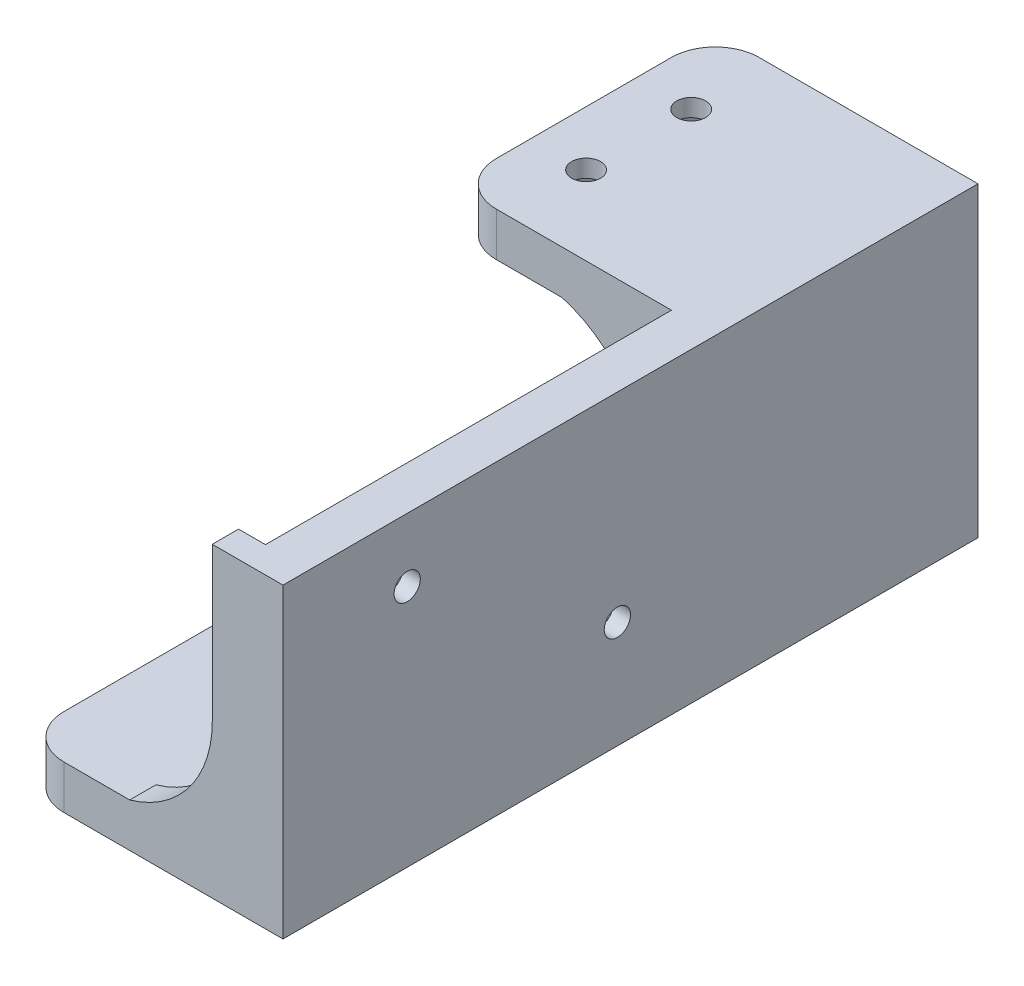
SolidWorks part; units mm, degrees
ref_plane "Спереди" through (0, 0, 0) normal (0, 0, 1) x (1, 0, 0)
ref_plane "Сверху" through (0, 0, 0) normal (0, 1, 0) x (1, 0, 0)
ref_plane "Справа" through (0, 0, 0) normal (1, 0, 0) x (0, 0, -1)
sketch "Эскиз1" plane through (0, 0, 0) normal (0, 0, 1) x (1, 0, 0)
  line L0 (0, 0) -> (30, 0)
  line L1 (30, 0) -> (30, 35)
  line L2 (30, 35) -> (0, 35)
  line L3 (0, 35) -> (0, 30)
  line L4 (0, 30) -> (25, 30)
  line L5 (25, 30) -> (25, 5)
  line L6 (25, 5) -> (0, 5)
  line L7 (0, 5) -> (0, 0)
  dimension "D1" = 35
  dimension "D2" = 5
  dimension "D3" = 5
  dimension "D4" = 5
  dimension "D5" = 30
extrude "Бобышка-Вытянуть1" add sketch "Эскиз1" along normal blind 30
sketch "Эскиз2" plane through (0, 0, 30) normal (0, 0, 1) x (1, 0, 0)
  line L0 (0, 30) -> (25, 30) construction
  line L1 (25, 5) -> (0, 5) construction
  line L2 (12.5, 30) -> (25, 30)
  line L3 (25, 30) -> (25, 5)
  line L4 (25, 5) -> (12.5, 5)
  arc A0 (12.5, 30) -> (12.5, 5) centre (8.9293, 17.5) cw
  dimension "D1" = 13
extrude "Бобышка-Вытянуть2" add sketch "Эскиз2" against normal blind 3
ref_plane "Плоскость1" through (0, 0, 15) normal (0, 0, 1) x (1, 0, 0)
mirror "Зеркальное отражение1" about plane through (0, 0, 15) normal (0, 0, 1) of "Бобышка-Вытянуть2"
sketch "Эскиз3" plane through (0, 5, 0) normal (0, 1, 0) x (1, 0, 0)
  line L0 (12.5, -3) -> (0, -3) construction
  line L1 (0, -30) -> (0, 0) construction
  line L2 (0, -3) -> (25, -27) construction
  line L3 (25, -15) -> (0, -15) construction
  line L4 (4.5179, -24) -> (2.7859, -21)
  line L5 (2.7859, -9) -> (4.5179, -12)
  line L6 (4.5179, -12) -> (7.9821, -12)
  line L7 (7.9821, -12) -> (9.7141, -9)
  line L8 (9.7141, -9) -> (7.9821, -6)
  line L9 (7.9821, -6) -> (4.5179, -6)
  line L10 (4.5179, -6) -> (2.7859, -9)
  line L17 (7.9821, -24) -> (4.5179, -24)
  line L18 (9.7141, -21) -> (7.9821, -24)
  line L19 (7.9821, -18) -> (9.7141, -21)
  line L20 (4.5179, -18) -> (7.9821, -18)
  line L21 (2.7859, -21) -> (4.5179, -18)
  circle A0 centre (6.25, -9) radius 3 construction
  point P10 (12.5, -15)
  dimension "D1" = 6
  dimension "D2" = 6
extrude "Вырез-Вытянуть1" cut sketch "Эскиз3" against normal blind 3
sketch "Эскиз4" plane through (0, 2, 0) normal (0, 1, 0) x (1, 0, 0)
  circle A0 centre (6.25, -21) radius 3.4641 construction
  circle A1 centre (6.25, -21) radius 1.65
  dimension "D1" = 3.3
extrude "Вырез-Вытянуть2" cut sketch "Эскиз4" against normal blind 17 and the other way blind 59
mirror "Зеркальное отражение2" about plane through (0, 0, 15) normal (0, 0, 1) of "Вырез-Вытянуть2"
sketch "Эскиз5" plane through (0, 30, 0) normal (0, -1, 0) x (1, 0, 0)
  line L1 (9.7141, 21) -> (7.9821, 24)
  line L2 (7.9821, 24) -> (4.5179, 24)
  line L3 (4.5179, 24) -> (2.7859, 21)
  line L4 (2.7859, 21) -> (4.5179, 18)
  line L5 (4.5179, 18) -> (7.9821, 18)
  line L6 (7.9821, 18) -> (9.7141, 21)
  circle A0 centre (6.25, 21) radius 3 construction
  dimension "D1" = 6
extrude "Вырез-Вытянуть3" cut sketch "Эскиз5" against normal blind 3
mirror "Зеркальное отражение3" about plane through (0, 0, 15) normal (0, 0, 1) of "Вырез-Вытянуть3"
fillet "Скругление1" radius 5 3 edges at (0, 32.5, 0) (0, 32.5, 30) (0, 2.5, 0)
sketch "Эскиз7" plane through (0, 0, 30) normal (0, 0, 1) x (1, 0, 0)
  line L0 (0, 0) -> (30, 0)
  line L1 (30, 0) -> (30, 35)
  line L2 (30, 35) -> (25, 35)
  line L3 (30, 35) -> (5, 35) construction
  line L4 (25, 35) -> (25, 5)
  line L5 (25, 5) -> (0, 5)
  line L6 (0, 5) -> (0, 0)
  line L7 (12.5, 5) -> (0, 5) construction
  dimension "D1" = 5
extrude "Бобышка-Вытянуть3" add sketch "Эскиз7" along normal blind 49.36
sketch "Эскиз8" plane through (0, 0, 79.36) normal (0, 0, 1) x (1, 0, 0)
  line L0 (21.9293, 17.5) -> (21.9293, 35)
  line L1 (25, 35) -> (5, 35) construction
  line L2 (21.9293, 35) -> (25, 35)
  line L3 (12.5, 5) -> (25, 5)
  line L4 (25, 5) -> (25, 35)
  arc A0 (12.5, 5) -> (12.5, 30) centre (8.9293, 17.5) ccw construction
  arc A1 (12.5, 5) -> (21.9293, 17.5) centre (8.9293, 17.5) ccw
extrude "Бобышка-Вытянуть4" add sketch "Эскиз8" against normal blind 3
sketch "Эскиз9" plane through (25, 0, 0) normal (-1, 0, 0) x (0, 0, 1)
  line L0 (76.36, 35) -> (30, 5) construction
  line L1 (53.18, 35) -> (53.18, 5) construction
  line L2 (76.36, 5) -> (30, 5) construction
  line L4 (65.18, 31.2294) -> (62.18, 29.4974)
  line L5 (62.18, 29.4974) -> (62.18, 26.0333)
  line L6 (62.18, 26.0333) -> (65.18, 24.3012)
  line L7 (65.18, 24.3012) -> (68.18, 26.0333)
  line L8 (68.18, 26.0333) -> (68.18, 29.4974)
  line L9 (68.18, 29.4974) -> (65.18, 31.2294)
  line L10 (41.18, 15.6988) -> (38.18, 13.9667)
  line L11 (38.18, 13.9667) -> (38.18, 10.5026)
  line L12 (38.18, 10.5026) -> (41.18, 8.7706)
  line L13 (41.18, 8.7706) -> (44.18, 10.5026)
  line L14 (44.18, 10.5026) -> (44.18, 13.9667)
  line L15 (44.18, 13.9667) -> (41.18, 15.6988)
  circle A0 centre (65.18, 27.7653) radius 3 construction
  circle A1 centre (41.18, 12.2347) radius 3 construction
  point P9 (53.18, 20)
  dimension "D1" = 6
  dimension "D2" = 12
  dimension "D3" = 6
  dimension "D4" = 12
extrude "Вырез-Вытянуть4" cut sketch "Эскиз9" against normal blind 3
sketch "Эскиз10" plane through (28, 0, 0) normal (-1, 0, 0) x (0, 0, 1)
  circle A0 centre (41.18, 12.2347) radius 3.4641 construction
  circle A1 centre (41.18, 12.2347) radius 1.5
  circle A2 centre (65.18, 27.7653) radius 3.4641 construction
  circle A3 centre (65.18, 27.7653) radius 1.5
  dimension "D1" = 3
extrude "Вырез-Вытянуть5" cut sketch "Эскиз10" against normal blind 12
fillet "Скругление2" radius 5 1 edges at (0, 2.5, 79.36)
sketch "Эскиз11" plane through (0, 5, 0) normal (0, 1, 0) x (1, 0, 0)
  line L0 (25, -76.36) -> (0, -76.36) construction
  line L1 (0, -76.36) -> (0, -30) construction
  line L2 (0, -74.36) -> (0, -5) construction
  line L3 (0, -30) -> (25, -30) construction
  line L4 (25, -76.36) -> (0, -30) construction
  line L6 (15.0648, -64.36) -> (16.7969, -67.36)
  line L7 (16.7969, -67.36) -> (20.261, -67.36)
  line L8 (20.261, -67.36) -> (21.993, -64.36)
  line L9 (21.993, -64.36) -> (20.261, -61.36)
  line L10 (20.261, -61.36) -> (16.7969, -61.36)
  line L11 (16.7969, -61.36) -> (15.0648, -64.36)
  line L12 (9.9352, -42) -> (8.2031, -39)
  line L13 (8.2031, -39) -> (4.739, -39)
  line L14 (4.739, -39) -> (3.007, -42)
  line L15 (3.007, -42) -> (4.739, -45)
  line L16 (4.739, -45) -> (8.2031, -45)
  line L17 (8.2031, -45) -> (9.9352, -42)
  circle A0 centre (18.5289, -64.36) radius 3 construction
  circle A1 centre (6.4711, -42) radius 3 construction
  dimension "D1" = 6
  dimension "D2" = 12
  dimension "D3" = 12
extrude "Вырез-Вытянуть6" cut sketch "Эскиз11" against normal blind 3
sketch "Эскиз12" plane through (0, 2, 0) normal (0, 1, 0) x (1, 0, 0)
  circle A0 centre (6.4711, -42) radius 3.4641 construction
  circle A1 centre (18.5289, -64.36) radius 3.4641 construction
  circle A2 centre (6.4711, -42) radius 1.65
  circle A3 centre (18.5289, -64.36) radius 1.65
  dimension "D1" = 3.3
extrude "Вырез-Вытянуть7" cut sketch "Эскиз12" against normal blind 15
